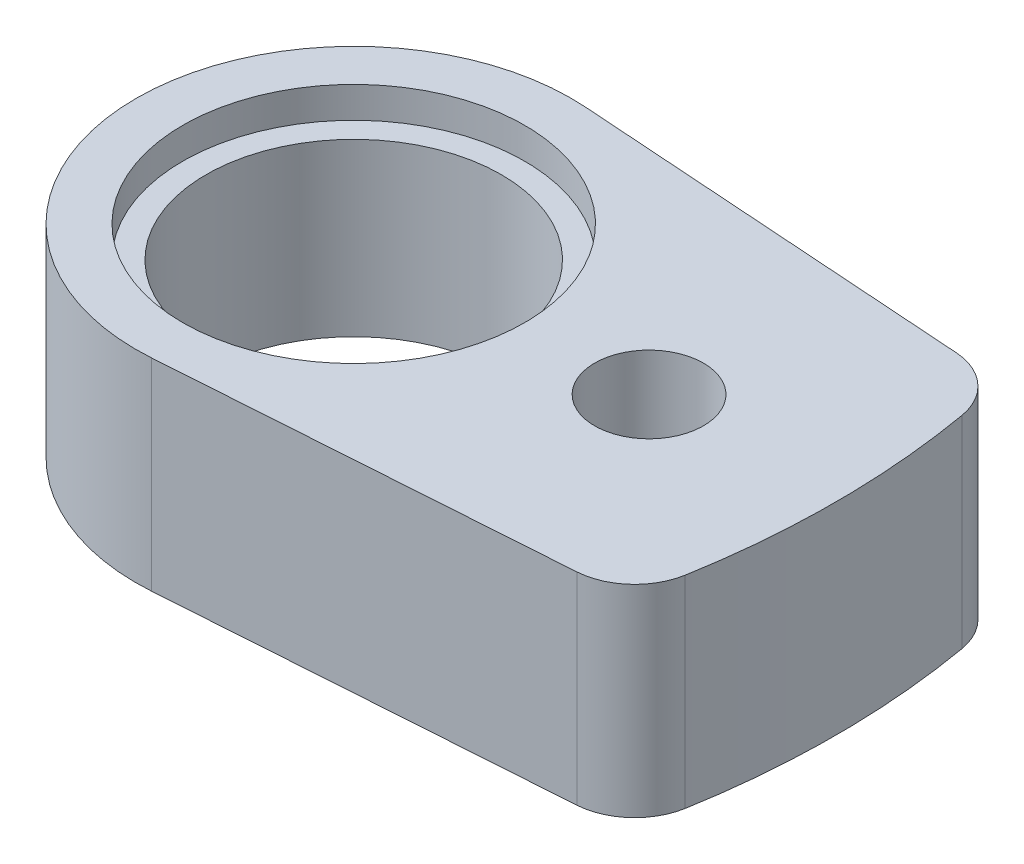
SolidWorks part; units mm, degrees
ref_plane "Front Plane" through (0, 0, 0) normal (0, 0, 1) x (1, 0, 0)
ref_plane "Top Plane" through (0, 0, 0) normal (0, 1, 0) x (1, 0, 0)
ref_plane "Right Plane" through (0, 0, 0) normal (1, 0, 0) x (0, 0, -1)
sketch "Sketch1" plane through (0, 0, 0) normal (0, 1, 0) x (1, 0, 0)
  line L0 (0.9594, 13.9671) -> (29.5964, 12)
  line L1 (29.5964, -12) -> (0.9594, -13.9671)
  circle A0 centre (0, 0) radius 9.5
  arc A2 (29.5964, 12) -> (29.5964, -12) centre (-21, 0) cw
  arc A3 (0.9594, -13.9671) -> (0.9594, 13.9671) centre (0, 0) cw
  circle A4 centre (19, 0) radius 3.5
  dimension "D1" = 4.5
  dimension "D3" = 19
  dimension "D4" = 52
  dimension "D5" = 24
  dimension "D6" = 19
  dimension "D7" = 40
  dimension "D2" = 7
extrude "Boss-Extrude1" add sketch "Sketch1" along normal blind 13
fillet "Fillet1" radius 4 2 edges at (29.5964, 6.5, 12) (29.5964, 6.5, -12)
sketch "Sketch3" plane through (0, 13, 0) normal (0, 1, 0) x (1, 0, 0)
  circle A0 centre (0, 0) radius 11
  dimension "D1" = 22
extrude "Cut-Extrude1" cut sketch "Sketch3" against normal blind 2
